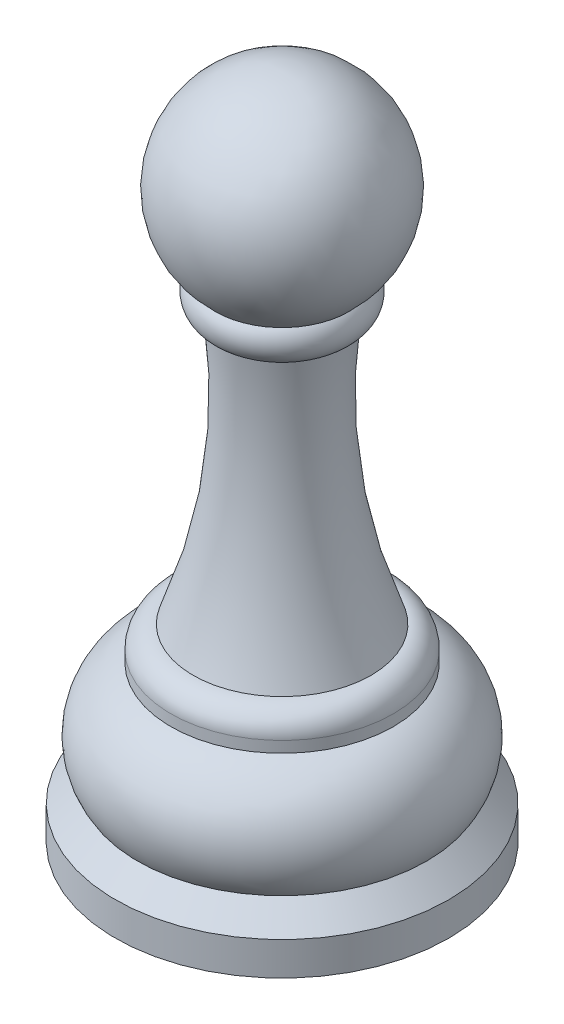
SolidWorks part; units mm, degrees
ref_plane "Front Plane" through (0, 0, 0) normal (0, 0, 1) x (1, 0, 0)
ref_plane "Top Plane" through (0, 0, 0) normal (0, 1, 0) x (1, 0, 0)
ref_plane "Right Plane" through (0, 0, 0) normal (1, 0, 0) x (0, 0, -1)
sketch "Sketch1" plane through (0, 0, 0) normal (0, 0, 1) x (1, 0, 0)
  line L0 (0, 0) -> (0, 60) construction
  line L1 (0, 0) -> (-15, 0)
  line L2 (-15, 0) -> (-15, 3)
  line L3 (-15, 3) -> (-13, 5)
  line L4 (-10, 13.97) -> (-10, 14.97)
  line L5 (0, 0) -> (0, 60)
  arc A0 (-13, 5) -> (-10, 13.97) centre (-7.9981, 8.3138) cw
  arc A1 (-10, 14.97) -> (-8, 16.97) centre (-8, 14.97) cw
  arc A2 (-8, 16.97) -> (-5, 41.03) centre (-54.6353, 35.0019) ccw
  arc A3 (-5, 41.03) -> (-6, 44.29) centre (-4.5005, 42.9666) cw
  arc A4 (-6, 44.29) -> (0, 60) centre (0, 50.9992) cw
  dimension "D7" = 6
  dimension "D10" = 2
  dimension "D14" = 50
  dimension "D17" = 2
  dimension "D1" = 60
  dimension "D2" = 30
  dimension "D3" = 3
  dimension "D4" = 2
  dimension "D5" = 45
  dimension "D6" = 20
  dimension "D8" = 8.97
  dimension "D9" = 1
  dimension "D11" = 16
  dimension "D12" = 24.06
  dimension "D13" = 10
  dimension "D15" = 12
  dimension "D16" = 3.26
revolve "Revolve3" add sketch "Sketch1" angle 360 about L0
